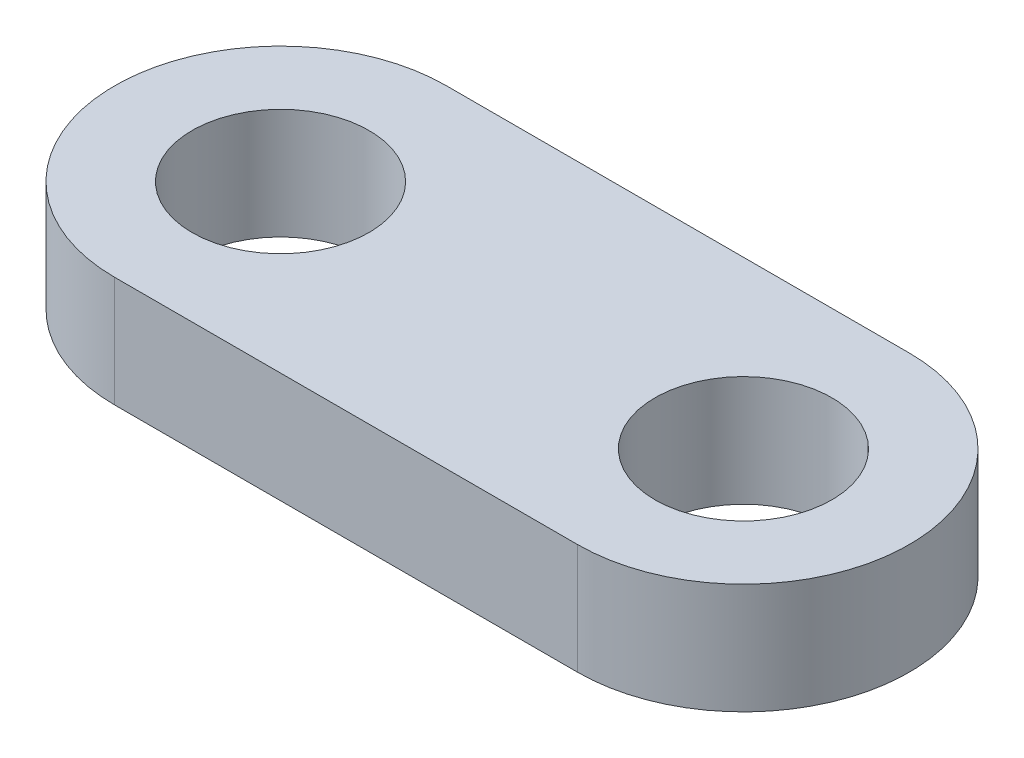
SolidWorks part; units mm, degrees
ref_plane "Front Plane" through (0, 0, 0) normal (0, 0, 1) x (1, 0, 0)
ref_plane "Top Plane" through (0, 0, 0) normal (0, 1, 0) x (1, 0, 0)
ref_plane "Right Plane" through (0, 0, 0) normal (1, 0, 0) x (0, 0, -1)
sketch "Sketch1" plane through (0, 0, 0) normal (0, 1, 0) x (1, 0, 0)
  line L0 (0, 7.5) -> (20.93, 7.5)
  line L1 (0, -7.5) -> (20.93, -7.5)
  arc A0 (0, 7.5) -> (0, -7.5) centre (0, 0) ccw
  arc A1 (20.93, -7.5) -> (20.93, 7.5) centre (20.93, 0) ccw
  circle A2 centre (20.93, 0) radius 4
  circle A3 centre (0, 0) radius 4
  dimension "D1" = 15
  dimension "D2" = 15
  dimension "D3" = 8
  dimension "D4" = 8
  dimension "D5" = 20.93
extrude "Boss-Extrude1" add sketch "Sketch1" along normal blind 5
scale "Scale1" scale about centroid uniform scaling yes scale factor 0.7
